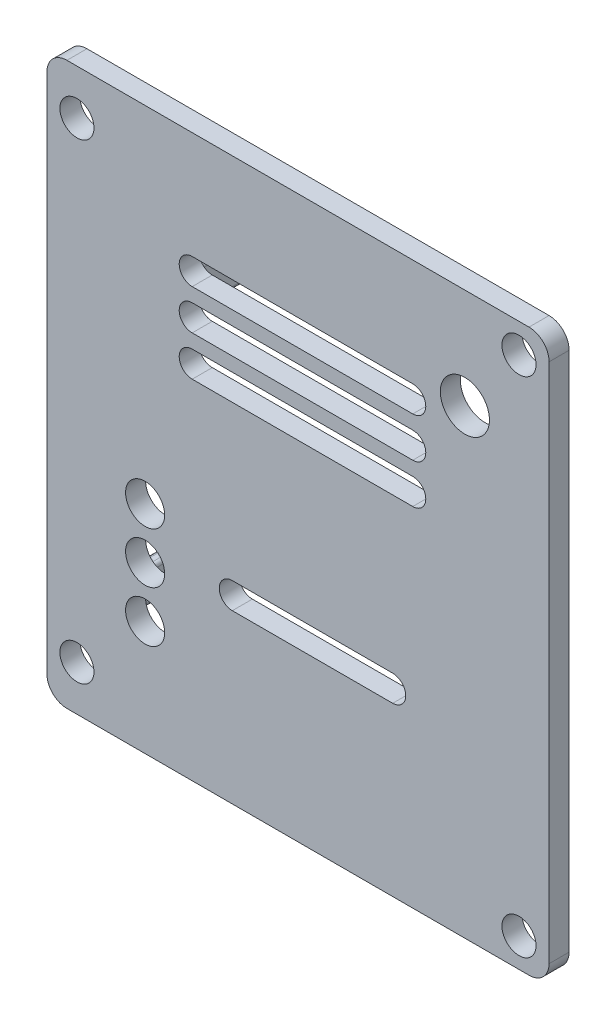
SolidWorks part; units mm, degrees
ref_plane "前视基准面" through (0, 0, 0) normal (0, 0, 1) x (1, 0, 0)
ref_plane "上视基准面" through (0, 0, 0) normal (0, 1, 0) x (1, 0, 0)
ref_plane "右视基准面" through (0, 0, 0) normal (1, 0, 0) x (0, 0, -1)
other "Configuration Table"
sketch "Clear_guard_2mm_Sketch" plane through (0, 0, 0) normal (0, 0, 1) x (1, 0, 0)
  line L0 (-26.5, -28) -> (19.6, -28)
  line L1 (21.6, -26) -> (21.6, 26)
  line L2 (19.6, 28) -> (-26.5, 28)
  line L3 (-28.5, 26) -> (-28.5, -26)
  arc A0 (19.6, -28) -> (21.6, -26) centre (19.6, -26) ccw
  arc A1 (21.6, 26) -> (19.6, 28) centre (19.6, 26) ccw
  arc A2 (-26.5, 28) -> (-28.5, 26) centre (-26.5, 26) ccw
  arc A3 (-28.5, -26) -> (-26.5, -28) centre (-26.5, -26) ccw
  circle A4 centre (-25.5, -23.5) radius 1.7
  circle A5 centre (18.6, -25.1) radius 1.7
  circle A6 centre (-25.5, 23.5) radius 1.7
  circle A7 centre (18.6, 25.1) radius 1.7
extrude "Clear_guard_2mm" add sketch "Clear_guard_2mm_Sketch" along normal blind 2 separate body
sketch "Openings_vent_and_trim_access_Sketch" plane through (0, 0, 0) normal (0, 0, 1) x (1, 0, 0)
  line L0 (-14, 6.7) -> (8, 6.7)
  line L1 (8, 9.3) -> (-14, 9.3)
  line L2 (-14, 10.7) -> (8, 10.7)
  line L3 (8, 13.3) -> (-14, 13.3)
  line L4 (-14, 14.7) -> (8, 14.7)
  line L5 (8, 17.3) -> (-14, 17.3)
  line L6 (-10, -11.3) -> (6, -11.3)
  line L7 (6, -8.7) -> (-10, -8.7)
  arc A0 (8, 6.7) -> (8, 9.3) centre (8, 8) ccw
  arc A1 (-14, 9.3) -> (-14, 6.7) centre (-14, 8) ccw
  arc A2 (8, 10.7) -> (8, 13.3) centre (8, 12) ccw
  arc A3 (-14, 13.3) -> (-14, 10.7) centre (-14, 12) ccw
  arc A4 (8, 14.7) -> (8, 17.3) centre (8, 16) ccw
  arc A5 (-14, 17.3) -> (-14, 14.7) centre (-14, 16) ccw
  circle A6 centre (13.2, 18) radius 2.45
  circle A7 centre (-18.7, -16.58) radius 1.95
  circle A8 centre (-18.7, -11.5) radius 1.95
  circle A9 centre (-18.7, -6.42) radius 1.95
  arc A10 (6, -11.3) -> (6, -8.7) centre (6, -10) ccw
  arc A11 (-10, -8.7) -> (-10, -11.3) centre (-10, -10) ccw
extrude "Openings_vent_and_trim_access" cut sketch "Openings_vent_and_trim_access_Sketch" along normal blind 2
sketch "PCB_end_stops_Sketch" plane through (0, 0, 0) normal (0, 0, 1) x (1, 0, 0)
  line L0 (-22.7, 4.5) -> (-22.2, 4.5)
  line L1 (-21.85, 4.85) -> (-21.85, 7.95)
  line L2 (-22.2, 8.3) -> (-22.7, 8.3)
  line L3 (-23.05, 7.95) -> (-23.05, 4.85)
  line L4 (-24.7, -20.6) -> (-24.2, -20.6)
  line L5 (-23.85, -20.25) -> (-23.85, -17.65)
  line L6 (-24.2, -17.3) -> (-24.7, -17.3)
  line L7 (-25.05, -17.65) -> (-25.05, -20.25)
  arc A0 (-22.2, 4.5) -> (-21.85, 4.85) centre (-22.2, 4.85) ccw
  arc A1 (-21.85, 7.95) -> (-22.2, 8.3) centre (-22.2, 7.95) ccw
  arc A2 (-22.7, 8.3) -> (-23.05, 7.95) centre (-22.7, 7.95) ccw
  arc A3 (-23.05, 4.85) -> (-22.7, 4.5) centre (-22.7, 4.85) ccw
  arc A4 (-24.2, -20.6) -> (-23.85, -20.25) centre (-24.2, -20.25) ccw
  arc A5 (-23.85, -17.65) -> (-24.2, -17.3) centre (-24.2, -17.65) ccw
  arc A6 (-24.7, -17.3) -> (-25.05, -17.65) centre (-24.7, -17.65) ccw
  arc A7 (-25.05, -20.25) -> (-24.7, -20.6) centre (-24.7, -20.25) ccw
extrude "PCB_end_stops" add sketch "PCB_end_stops_Sketch" along normal blind 14.5 from offset 14.5
